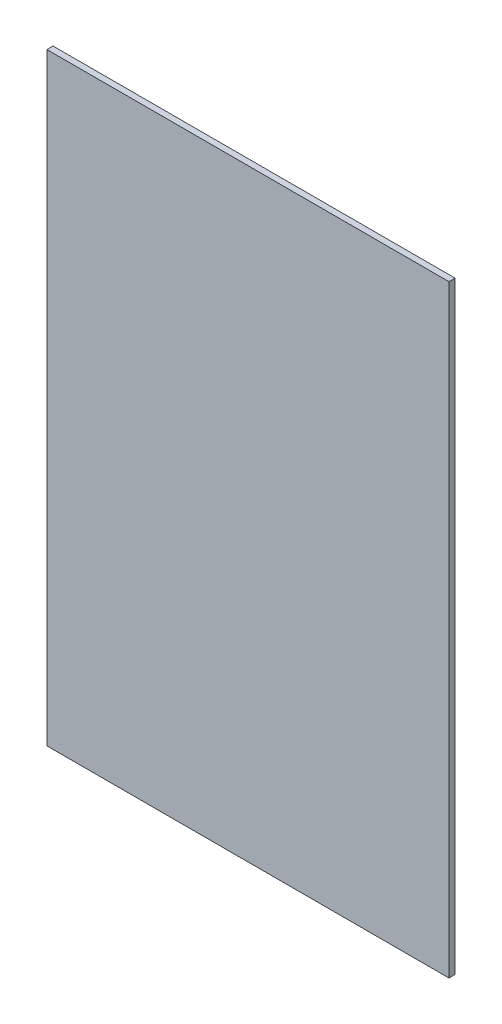
SolidWorks part; units mm, degrees
material "Printed Circuit Board"
ref_plane "Front Plane" through (0, 0, 0) normal (0, 0, 1) x (1, 0, 0)
ref_plane "Top Plane" through (0, 0, 0) normal (0, 1, 0) x (1, 0, 0)
ref_plane "Right Plane" through (0, 0, 0) normal (1, 0, 0) x (0, 0, -1)
sketch "Sketch1" plane through (0, 0, 0) normal (0, 0, 1) x (1, 0, 0)
  line L1 (-50, -75) -> (50, -75)
  line L2 (-50, -75) -> (-50, 75)
  line L3 (-50, 75) -> (50, 75)
  line L4 (50, -75) -> (50, 75)
  line L5 (-50, -75) -> (50, 75) construction
  line L6 (-50, 75) -> (50, -75) construction
  point P0 (0, 0)
  dimension "D1" = 100
  dimension "D2" = 150
extrude "Extrude1" add sketch "Sketch1" along normal blind 1.524
sketch "Sketch2" plane through (0, 75, 0) normal (0, 1, 0) x (1, 0, 0)
  line L0 (50, 0) -> (-50, 0) construction
  line L1 (50, -1.524) -> (-50, -1.524) construction
  point P0 (0, 0)
  point P1 (0, -1.524)
